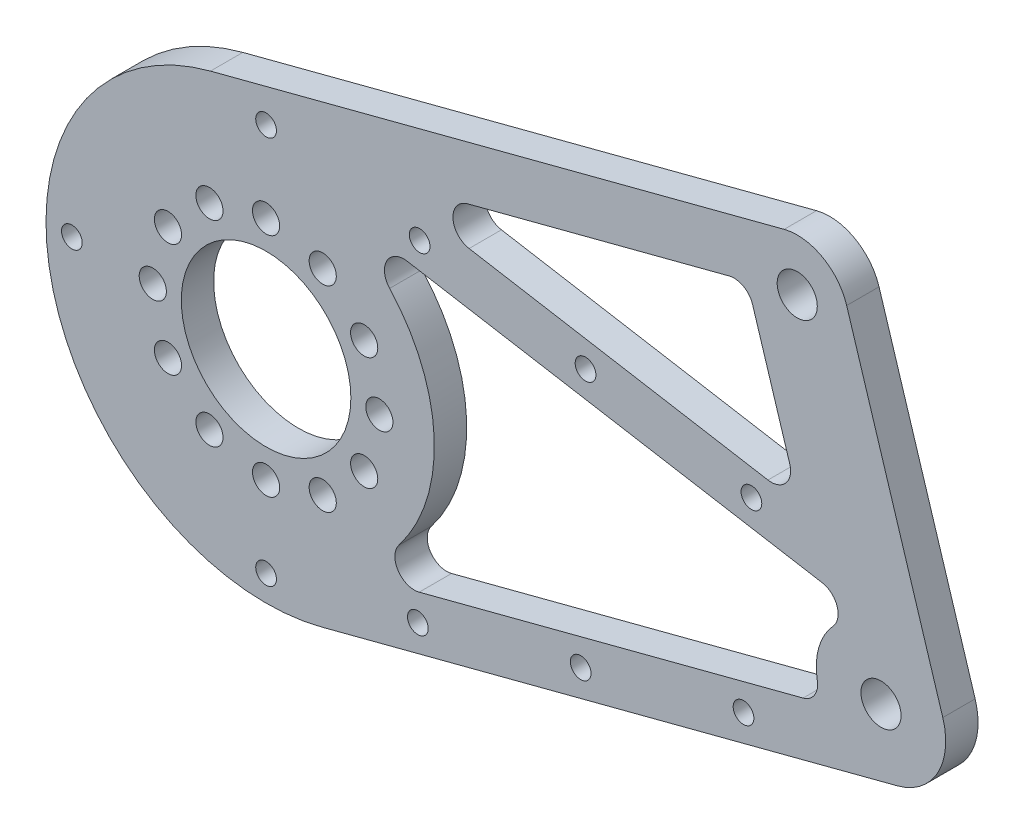
SolidWorks part; units mm, degrees
material "Thornel Mat VMA"
ref_plane "前视基准面" through (0, 0, 0) normal (0, 0, 1) x (1, 0, 0)
ref_plane "上视基准面" through (0, 0, 0) normal (0, 1, 0) x (1, 0, 0)
ref_plane "右视基准面" through (0, 0, 0) normal (1, 0, 0) x (0, 0, -1)
sketch "草图1" plane through (0, 0, 0) normal (0, 0, 1) x (1, 0, 0)
  line L0 (-12.941, 48.2963) -> (0, 0) construction
  line L1 (0, 0) -> (-95, 0) construction
  line L2 (-95, 0) -> (-12.941, 48.2963) construction
  line L3 (-103.5891, 32.8972) -> (-14.9619, 56.0368)
  line L4 (-5.3026, 50.6743) -> (9.548, 2.9725)
  line L5 (-86.4105, -32.8971) -> (2.5263, -9.6756)
  circle A0 centre (0, 0) radius 3.1
  circle A1 centre (-95, 0) radius 13.1
  circle A2 centre (-12.941, 48.2963) radius 3.1
  arc A3 (2.5263, -9.6756) -> (9.548, 2.9725) centre (0, 0) ccw
  arc A5 (-5.3026, 50.6743) -> (-14.9619, 56.0368) centre (-12.941, 48.2963) ccw
  circle A6 centre (-95, 0) radius 26 construction
  arc A9 (-103.5891, 32.8972) -> (-86.4105, -32.8971) centre (-95, 0) ccw
  circle A10 centre (-95, 0) radius 30 construction
  circle A11 centre (-95, 30) radius 1.6
  circle A12 centre (-125, 0) radius 1.6
  circle A13 centre (-95, -30) radius 1.6
  circle A14 centre (-95, 0) radius 34 construction
  circle A15 centre (-95, 0) radius 17.5 construction
  dimension "D3" = 6.2
  dimension "D4" = 26.2
  dimension "D5" = 6.2
  dimension "D6" = 16
  dimension "D7" = 20
  dimension "D8" = 8
  dimension "D9" = 52
  dimension "D10" = 4
  dimension "D11" = 3.2
  dimension "D12" = 68
  dimension "D13" = 35
  dimension "D1" = 50
  dimension "D2" = 95
  dimension "D14" = 75
extrude "凸台-拉伸1" add sketch "草图1" along normal blind 5 contours L3 A9 L5 A3 L4 A5 A15 A13 A12 A11 A0 A2
sketch "草图3" plane through (0, 0, 5) normal (0, 0, 1) x (1, 0, 0)
  line L0 (-95, 0) -> (-95, 17.5) construction
  line L1 (-95, 0) -> (-86.25, 15.1554) construction
  circle A0 centre (-95, 0) radius 17.5 construction
  circle A1 centre (-95, 17.5) radius 2.1
  circle A2 centre (-86.25, 15.1554) radius 2.1
  circle A3 centre (-79.8446, 8.75) radius 2.1
  circle A4 centre (-77.5, 0) radius 2.1
  circle A5 centre (-79.8446, -8.75) radius 2.1
  circle A6 centre (-86.25, -15.1554) radius 2.1
  circle A7 centre (-95, -17.5) radius 2.1
  circle A8 centre (-103.75, -15.1554) radius 2.1
  circle A9 centre (-110.1554, -8.75) radius 2.1
  circle A10 centre (-112.5, 0) radius 2.1
  circle A11 centre (-110.1554, 8.75) radius 2.1
  circle A12 centre (-103.75, 15.1554) radius 2.1
  dimension "D1" = 35
  dimension "D2" = 4.2
  dimension "D4" = 30
  dimension "D3" = 12
extrude "切除-拉伸1" cut sketch "草图3" against normal blind 34
sketch "草图4" plane through (0, 0, 5) normal (0, 0, 1) x (1, 0, 0)
  line L0 (-90.6211, 25.6286) -> (1.6842, 9.8572)
  line L1 (-88.4316, -25.1566) -> (0, 10) construction
  line L2 (-8.9749, -4.4104) -> (-88.4316, -25.1566)
  line L3 (-86.4105, -32.8971) -> (2.5263, -9.6756) construction
  arc A0 (-88.4316, -25.1566) -> (-90.6211, 25.6286) centre (-95, 0) ccw
  arc A2 (1.6842, 9.8572) -> (-8.9749, -4.4104) centre (0, 0) ccw
  dimension "D1" = 52
  dimension "D3" = 20
extrude "切除-拉伸2" cut sketch "草图4" against normal blind 24
fillet "圆角1" radius 3 4 edges at (-8.9749, -4.4104, 2.5) (1.6842, 9.8572, 2.5) (-90.6211, 25.6286, 2.5) (-88.4316, -25.1566, 2.5)
sketch "草图5" plane through (0, 0, 5) normal (0, 0, 1) x (1, 0, 0)
  line L0 (-71.341, -20.6943) -> (-12.0358, -5.2096) construction
  line L4 (-5.3026, 50.6743) -> (9.548, 2.9725) construction
  line L5 (-8.4401, 15.645) -> (-72.5362, 26.5965)
  line L6 (6.3917, 13.1108) -> (-105.7188, 32.2662) construction
  circle A0 centre (-71.5518, -24.8834) radius 1.6
  circle A1 centre (-95, -30) radius 1.6 construction
  circle A2 centre (-46.3951, -18.315) radius 1.6
  circle A3 centre (-21.2385, -11.7465) radius 1.6
  arc A4 (-103.5891, 32.8972) -> (-86.4105, -32.8971) centre (-95, 0) ccw construction
  circle A5 centre (-71.2744, 26.381) radius 1.6
  circle A6 centre (-95, 30) radius 1.6 construction
  circle A7 centre (-45.6458, 22.002) radius 1.6
  circle A8 centre (-20.0172, 17.6231) radius 1.6
  dimension "D1" = 3.2
  dimension "D3" = 24
  dimension "D7" = 3.2
  dimension "D8" = 24
  dimension "D2" = 4
  dimension "D5" = 26
  dimension "D10" = 26
  dimension "D6" = 4
  dimension "D4" = 3
  dimension "D9" = 3
extrude "切除-拉伸3" cut sketch "草图5" against normal blind 24
sketch "草图6" plane through (0, 0, 5) normal (0, 0, 1) x (1, 0, 0)
  line L0 (-77.3564, 31.4781) -> (-20.6898, 46.2731)
  line L1 (-20.6898, 46.2731) -> (-12.6415, 20.4208)
  line L2 (-12.6415, 20.4208) -> (-77.3564, 31.4781)
  line L3 (-9.1138, 11.7021) -> (-73.2099, 22.6537) construction
  line L4 (-103.5891, 32.8972) -> (-14.9619, 56.0368) construction
  line L5 (-5.3026, 50.6743) -> (9.548, 2.9725) construction
  circle A0 centre (-12.941, 48.2963) radius 3.1 construction
  dimension "D1" = 8
  dimension "D2" = 8
  dimension "D3" = 8
extrude "切除-拉伸4" cut sketch "草图6" against normal blind 34
fillet "圆角2" radius 3 3 edges at (-77.3564, 31.4781, 2.5) (-12.6415, 20.4208, 2.5) (-20.6898, 46.2731, 2.5)
